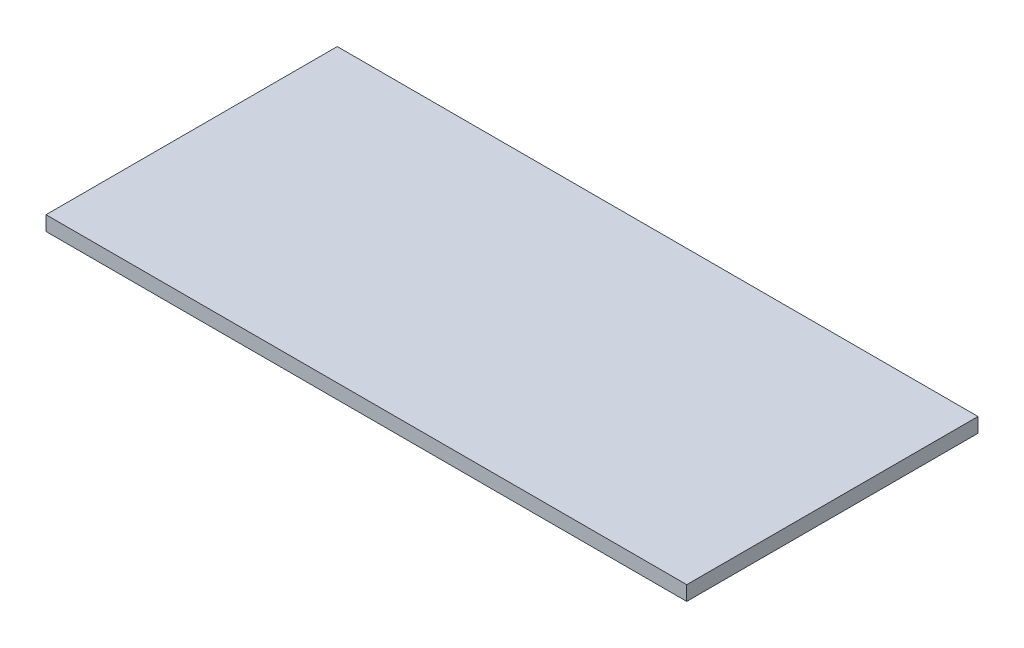
SolidWorks part; units mm, degrees
material "PE High Density"
ref_plane "Front Plane" through (0, 0, 0) normal (0, 0, 1) x (1, 0, 0)
ref_plane "Top Plane" through (0, 0, 0) normal (0, 1, 0) x (1, 0, 0)
ref_plane "Right Plane" through (0, 0, 0) normal (1, 0, 0) x (0, 0, -1)
sketch "Sketch1" plane through (0, 0, 0) normal (0, 1, 0) x (1, 0, 0)
  line L1 (0, 0) -> (139.7, 0)
  line L2 (0, 0) -> (0, 63.5)
  line L3 (0, 63.5) -> (139.7, 63.5)
  line L4 (139.7, 0) -> (139.7, 63.5)
  dimension "D1" = 63.5
  dimension "D2" = 139.7
extrude "Boss-Extrude1" add sketch "Sketch1" along normal blind 3.175
